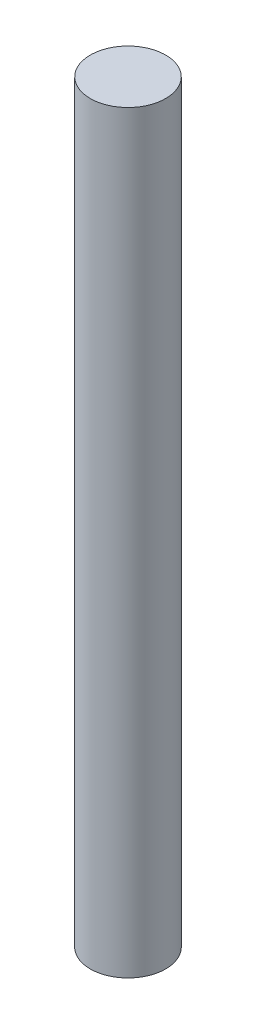
SolidWorks part; units mm, degrees
ref_plane "前视基准面" through (0, 0, 0) normal (0, 0, 1) x (1, 0, 0)
ref_plane "上视基准面" through (0, 0, 0) normal (0, 1, 0) x (1, 0, 0)
ref_plane "右视基准面" through (0, 0, 0) normal (1, 0, 0) x (0, 0, -1)
sketch "草图1" plane through (0, 0, 0) normal (0, 1, 0) x (1, 0, 0)
  circle A0 centre (0, 0) radius 10
  dimension "D1" = 20
extrude "凸台-拉伸1" add sketch "草图1" along normal blind 200
